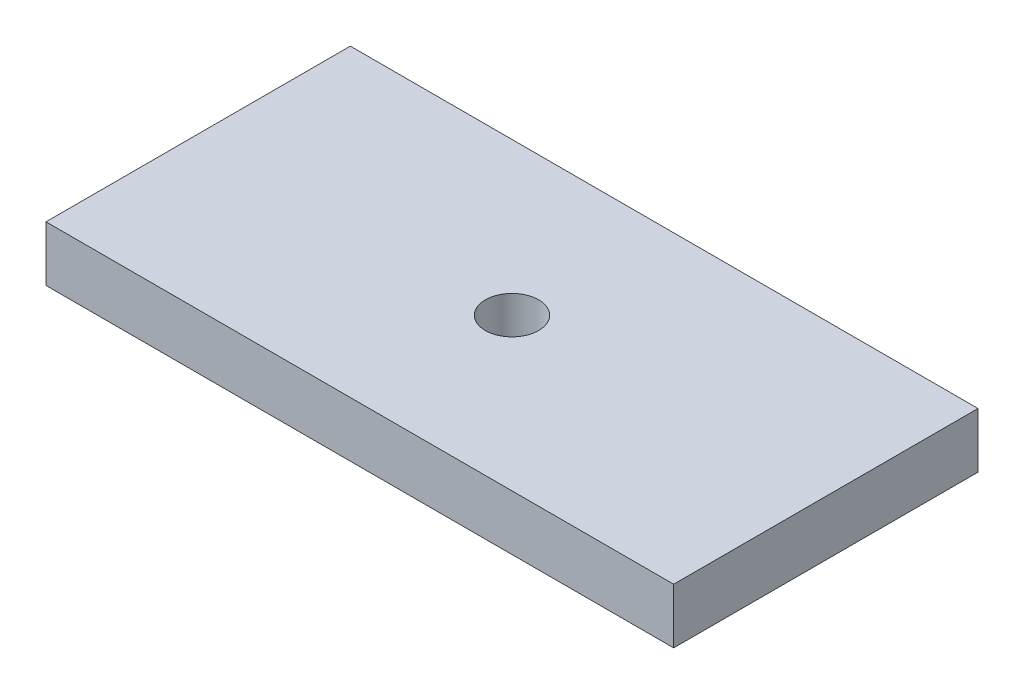
SolidWorks part; units mm, degrees
ref_plane "Front Plane" through (0, 0, 0) normal (0, 0, 1) x (1, 0, 0)
ref_plane "Top Plane" through (0, 0, 0) normal (0, 1, 0) x (1, 0, 0)
ref_plane "Right Plane" through (0, 0, 0) normal (1, 0, 0) x (0, 0, -1)
sketch "Sketch1" plane through (0, 0, 0) normal (0, 1, 0) x (1, 0, 0)
  line L1 (-8.25, -4) -> (8.25, -4)
  line L2 (-8.25, -4) -> (-8.25, 4)
  line L3 (-8.25, 4) -> (8.25, 4)
  line L4 (8.25, -4) -> (8.25, 4)
  line L5 (-8.25, -4) -> (8.25, 4) construction
  line L6 (-8.25, 4) -> (8.25, -4) construction
  circle A0 centre (0, 0) radius 0.7007
  point P0 (0, 0)
  dimension "D1" = 16.5
  dimension "D2" = 8
extrude "Boss-Extrude1" add sketch "Sketch1" along normal blind 1.45
